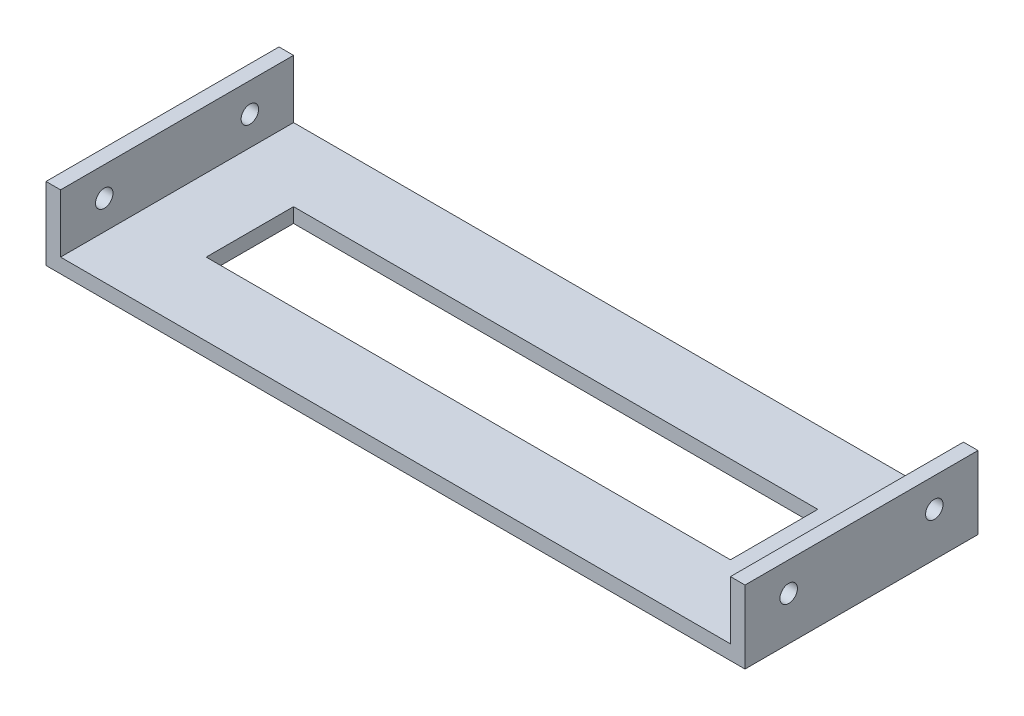
SolidWorks part; units mm, degrees
ref_plane "Front Plane" through (0, 0, 0) normal (0, 0, 1) x (1, 0, 0)
ref_plane "Top Plane" through (0, 0, 0) normal (0, 1, 0) x (1, 0, 0)
ref_plane "Right Plane" through (0, 0, 0) normal (1, 0, 0) x (0, 0, -1)
sketch "Sketch1" plane through (0, 0, 0) normal (0, 1, 0) x (1, 0, 0)
  line L1 (-120, -40) -> (120, -40)
  line L2 (-120, -40) -> (-120, 40)
  line L3 (-120, 40) -> (120, 40)
  line L4 (120, -40) -> (120, 40)
  line L5 (-120, -40) -> (120, 40) construction
  line L6 (-120, 40) -> (120, -40) construction
  line L7 (-90, 15) -> (90, 15)
  line L8 (-90, 15) -> (-90, -15)
  line L9 (-90, -15) -> (90, -15)
  line L10 (90, 15) -> (90, -15)
  line L11 (-90, 15) -> (90, -15) construction
  line L12 (-90, -15) -> (90, 15) construction
  point P0 (0, 0)
  point P6 (0, 0)
  dimension "D1" = 240
  dimension "D2" = 80
  dimension "D3" = 180
  dimension "D4" = 30
extrude "Boss-Extrude1" add sketch "Sketch1" along normal blind 5
sketch "Sketch2" plane through (0, 5, 0) normal (0, 1, 0) x (1, 0, 0)
  line L0 (-120, -40) -> (120, -40) construction
  line L1 (120, 40) -> (115, 40)
  line L2 (120, 40) -> (120, -40)
  line L3 (120, -40) -> (115, -40)
  line L4 (115, 40) -> (115, -40)
  dimension "D1" = 5
extrude "Boss-Extrude2" add sketch "Sketch2" along normal blind 20
sketch "Sketch4" plane through (0, 5, 0) normal (0, 1, 0) x (1, 0, 0)
  line L0 (-120, -40) -> (115, -40) construction
  line L1 (-120, 40) -> (-115, 40)
  line L2 (-120, 40) -> (-120, -40)
  line L3 (-120, -40) -> (-115, -40)
  line L4 (-115, 40) -> (-115, -40)
  dimension "D1" = 5
extrude "Boss-Extrude3" add sketch "Sketch4" along normal blind 20
sketch "Sketch3" plane through (120, 0, 0) normal (1, 0, 0) x (0, 0, -1)
  line L0 (0, 0) -> (0, -16.3166)
  line L1 (-40, 25) -> (40, 25) construction
  line L2 (-40, 25) -> (-40, 0) construction
  circle A0 centre (-25, 15) radius 3
  circle A1 centre (25, 15) radius 3
  dimension "D1" = 6
  dimension "D2" = 10
  dimension "D3" = 15
extrude "Cut-Extrude1" cut sketch "Sketch3" against normal through all contours A0 | A1
